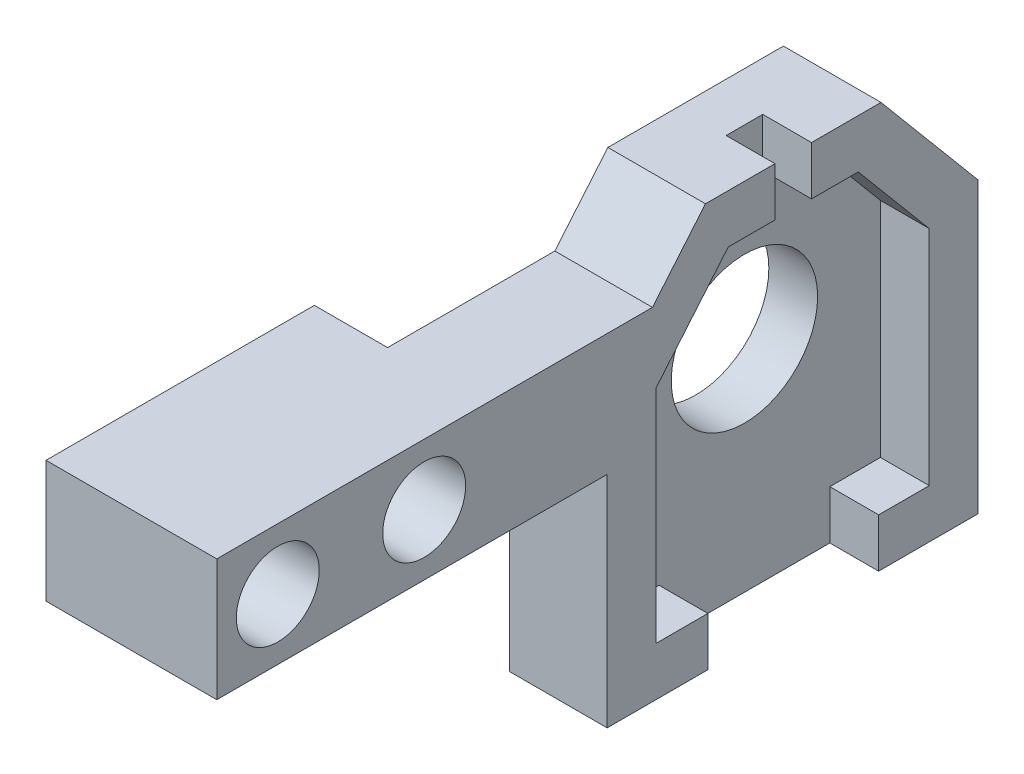
SolidWorks part; units mm, degrees
ref_plane "Front Plane" through (0, 0, 0) normal (0, 0, 1) x (1, 0, 0)
ref_plane "Top Plane" through (0, 0, 0) normal (0, 1, 0) x (1, 0, 0)
ref_plane "Right Plane" through (0, 0, 0) normal (1, 0, 0) x (0, 0, -1)
sketch "Sketch1" plane through (0, 0, 0) normal (1, 0, 0) x (0, 0, -1)
  line L0 (-6.1093, 3.9687) -> (-3.1473, 7.4987)
  line L1 (-3.1473, 7.4987) -> (-1.2321, 7.4987)
  line L2 (-6.1093, 3.9687) -> (-6.1093, -5.0913)
  line L3 (-6.1093, -5.0913) -> (-3.9821, -5.0913)
  line L4 (5.0907, 4.0335) -> (5.0907, -5.0913)
  line L5 (-4.0799, 9.4987) -> (-1.2321, 9.4987)
  line L6 (-8.1093, 4.6966) -> (-8.1093, -7.0913)
  line L7 (-8.1093, -7.0913) -> (-3.9821, -7.0913)
  line L8 (7.0907, 4.7614) -> (7.0907, -7.0913)
  line L9 (5.0907, 4.0335) -> (2.1831, 7.4987)
  line L10 (-8.1093, 4.6966) -> (-4.0799, 9.4987)
  line L11 (3.1157, 9.4987) -> (7.0907, 4.7614)
  line L12 (0.2679, 7.4987) -> (0.2679, 9.4987)
  line L13 (-1.2321, 7.4987) -> (-1.2321, 9.4987)
  line L14 (3.0179, -5.0913) -> (3.0179, -7.0913)
  line L15 (-3.9821, -5.0913) -> (-3.9821, -7.0913)
  line L16 (-0.4821, 1.9087) -> (-0.4821, -6.5913) construction
  line L17 (-8.1093, 1.9087) -> (7.0907, 1.9087) construction
  line L18 (0.2679, 9.4987) -> (3.1157, 9.4987)
  line L19 (0.2679, 7.4987) -> (2.1831, 7.4987)
  line L20 (3.0179, -5.0913) -> (5.0907, -5.0913)
  line L21 (3.0179, -7.0913) -> (7.0907, -7.0913)
  point P20 (1.2255, 7.4987)
  dimension "D1" = 2
  dimension "D2" = 2
  dimension "D3" = 2
  dimension "D4" = 2
  dimension "D5" = 2
  dimension "D6" = 2
  dimension "D7" = 40
  dimension "D8" = 40
  dimension "D9" = 3.53
  dimension "D10" = 3.5
  dimension "D11" = 7
  dimension "D12" = 3.5
  dimension "D13" = 0.75
  dimension "D14" = 0.75
  dimension "D15" = 5.59
  dimension "D16" = 11.2
sketch "Sketch2" plane through (0, 0, 0) normal (1, 0, 0) x (0, 0, -1)
  line L0 (-8.1093, -7.0913) -> (-8.1093, 4.6966)
  line L1 (-8.1093, 4.6966) -> (-4.0799, 9.4987)
  line L2 (-4.0799, 9.4987) -> (3.1157, 9.4987)
  line L3 (3.1157, 9.4987) -> (7.0907, 4.7614)
  line L4 (7.0907, 4.7614) -> (7.0907, -7.0913)
  line L5 (7.0907, -7.0913) -> (-8.1093, -7.0913)
extrude "Boss-Extrude1" add sketch "Sketch2" against normal blind 2
extrude "Boss-Extrude2" add sketch "Sketch1" along normal blind 2
sketch "Sketch3" plane through (0, 0, 0) normal (1, 0, 0) x (0, 0, -1)
  circle A0 centre (-0.4821, 1.9087) radius 3
extrude "Cut-Extrude1" cut sketch "Sketch3" against normal blind 2
sketch "Sketch4" plane through (2, 0, 0) normal (1, 0, 0) x (0, 0, -1)
  line L0 (-15.4821, 1.9087) -> (-8.1093, 1.9087)
  line L7 (-6.2532, 6.9087) -> (-20.486, 6.9087)
  line L19 (-8.1093, 4.6966) -> (-8.1093, 1.9087)
  line L20 (-8.1093, 4.6966) -> (-6.2532, 6.9087)
  line L21 (-4.0799, 9.4987) -> (-8.1093, 4.6966) construction
  line L22 (-15.4821, 1.9087) -> (-24.1093, 1.9087)
  line L23 (-24.1093, 1.9087) -> (-24.1093, 6.9087)
  line L24 (-24.1093, 6.9087) -> (-20.486, 6.9087)
  circle A0 centre (-15.6093, 4.4087) radius 1.7
  circle A2 centre (-21.6093, 4.4087) radius 1.7
  dimension "D7" = 3.4
  dimension "D6" = 3.4
  dimension "D1" = 5
  dimension "D3" = 2.5
  dimension "D4" = 2.5
  dimension "D5" = 6
extrude "Boss-Extrude3" add sketch "Sketch4" against normal blind 7
sketch "Sketch5" plane through (-5, 0, 0) normal (-1, 0, 0) x (0, 0, 1)
  line L7 (6.2532, 6.9087) -> (24.1093, 6.9087) construction
  line L8 (8.1093, 6.9087) -> (6.2532, 6.9087)
  line L9 (6.2532, 6.9087) -> (8.1093, 4.6966)
  line L10 (8.1093, 6.9087) -> (13.1093, 6.9087)
  line L11 (13.1093, 6.9087) -> (13.1093, 1.9087)
  line L12 (24.1093, 1.9087) -> (8.1093, 1.9087) construction
  line L13 (13.1093, 1.9087) -> (8.1093, 1.9087)
  line L14 (8.1093, 1.9087) -> (8.1093, 4.6966)
  circle A0 centre (15.6093, 4.4087) radius 1.7 construction
  dimension "D1" = 2.5
extrude "Cut-Extrude2" cut sketch "Sketch5" against normal blind 3
